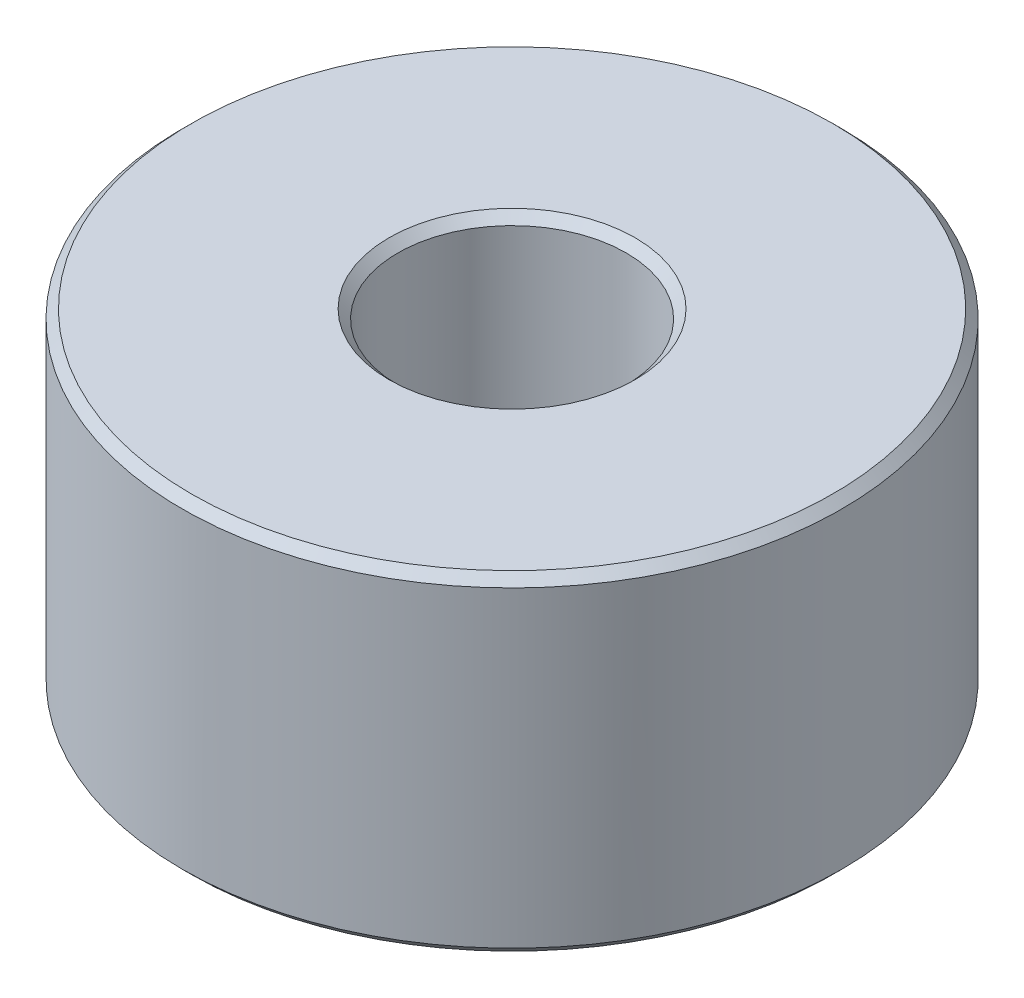
SolidWorks part; units mm, degrees
ref_plane "Front Plane" through (0, 0, 0) normal (0, 0, 1) x (1, 0, 0)
ref_plane "Top Plane" through (0, 0, 0) normal (0, 1, 0) x (1, 0, 0)
ref_plane "Right Plane" through (0, 0, 0) normal (1, 0, 0) x (0, 0, -1)
sketch "Sketch1" plane through (0, 0, 0) normal (0, 1, 0) x (1, 0, 0)
  circle A0 centre (0, 0) radius 7.5
  circle A1 centre (0, 0) radius 2.6
  dimension "D1" = 15
  dimension "D2" = 5.2
extrude "Boss-Extrude1" add sketch "Sketch1" along normal blind 7.5
chamfer "Chamfer1" distance 0.2 angle 45 4 edges at (0, 0, 2.6) (0, 0, 7.5) (0, 7.5, 2.6) (0, 7.5, 7.5)
